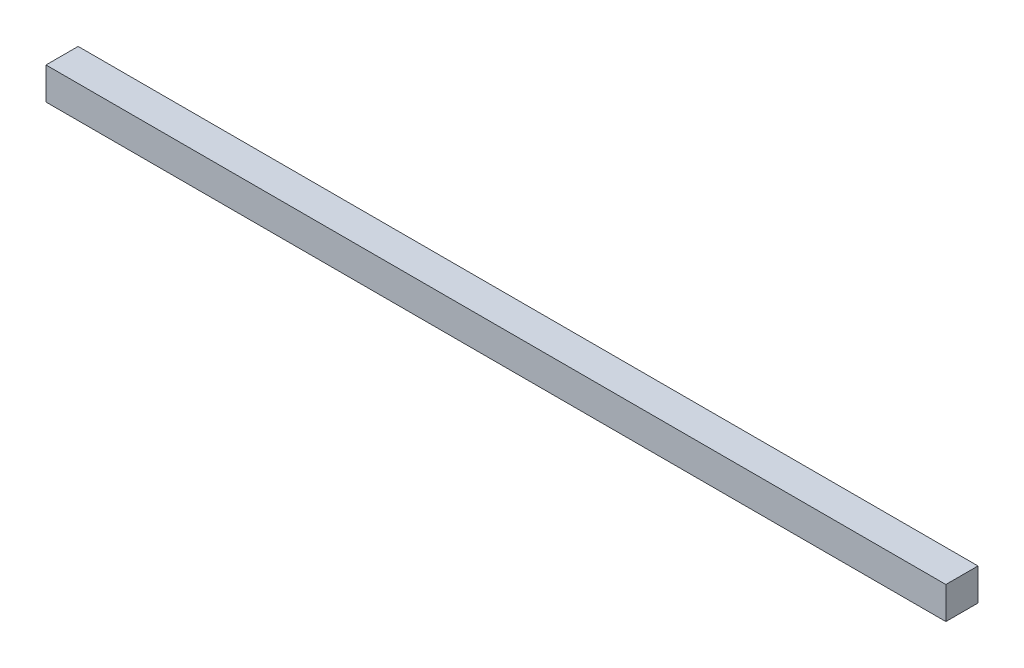
SolidWorks part; units mm, degrees
ref_plane "前视基准面" through (0, 0, 0) normal (0, 0, 1) x (1, 0, 0)
ref_plane "上视基准面" through (0, 0, 0) normal (0, 1, 0) x (1, 0, 0)
ref_plane "右视基准面" through (0, 0, 0) normal (1, 0, 0) x (0, 0, -1)
other "Configuration Table"
sketch "草图1" plane through (0, 0, 0) normal (0, 0, 1) x (1, 0, 0)
  line L0 (0, 0) -> (700, 0)
  line L1 (700, 0) -> (700, 25)
  line L2 (700, 25) -> (0, 25)
  line L3 (0, 25) -> (0, 0)
  dimension "width" = 700
  dimension "height" = 25
extrude "BlockExtrude" add sketch "草图1" along normal blind 25
